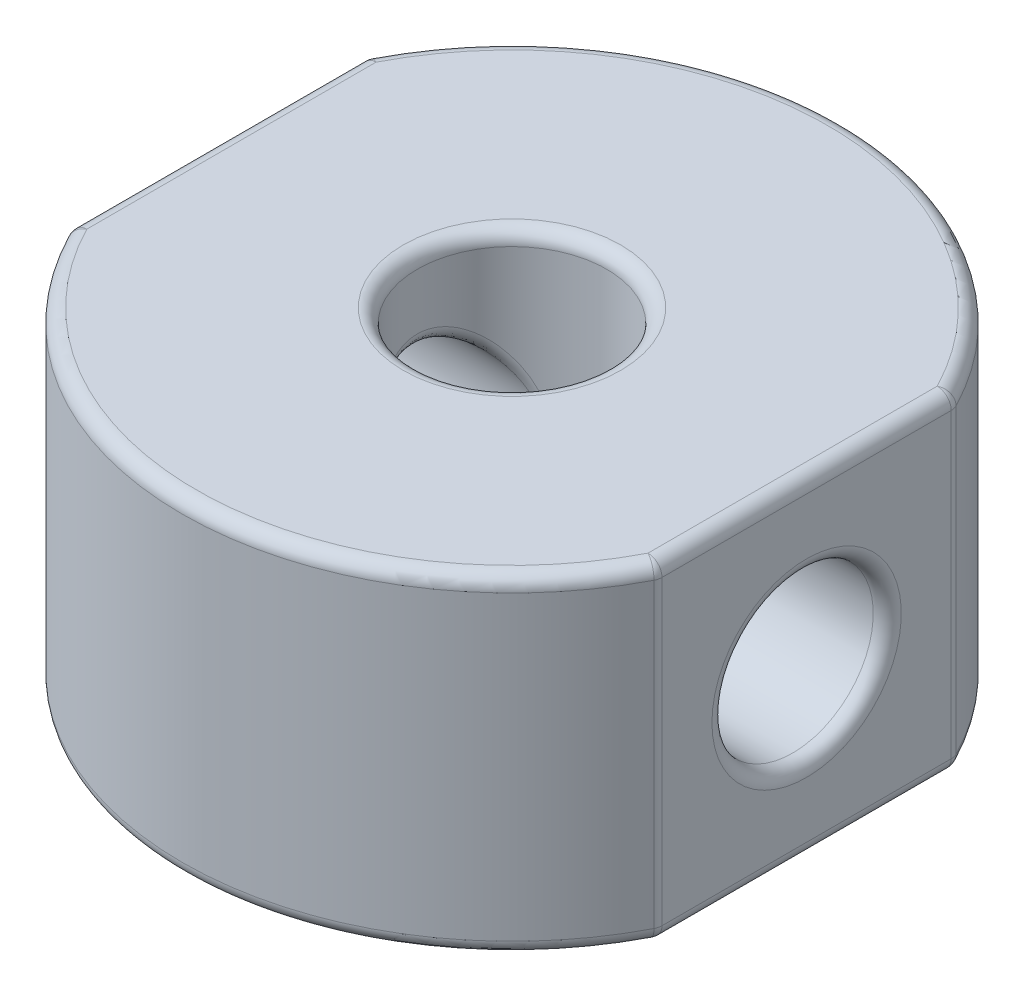
SolidWorks part; units mm, degrees
ref_plane "Front Plane" through (0, 0, 0) normal (0, 0, 1) x (1, 0, 0)
ref_plane "Top Plane" through (0, 0, 0) normal (0, 1, 0) x (1, 0, 0)
ref_plane "Right Plane" through (0, 0, 0) normal (1, 0, 0) x (0, 0, -1)
sketch "Sketch1" plane through (0, 0, 0) normal (0, 1, 0) x (1, 0, 0)
  line L0 (-2.7, 0) -> (-8.4, 0) construction
  line L1 (2.7, 0) -> (8.4, 0) construction
  line L2 (8.4, -4.219) -> (8.4, 4.219)
  line L3 (-8.4, -4.219) -> (-8.4, 4.219)
  line L4 (-8.4, 0) -> (-9.4, 0) construction
  circle A0 centre (0, 0) radius 9.4
  circle A1 centre (0, 0) radius 2.7
  point P11 (8.4, 0)
  point P14 (-8.4, 0)
  dimension "D1" = 5.4
  dimension "D2" = 5.7
  dimension "D3" = 1
extrude "Boss-Extrude1" add sketch "Sketch1" along normal blind 9.4 contours L2 A0 L3 A1
sketch "Sketch2" plane through (-8.4, 0, 0) normal (-1, 0, 0) x (0, 0, 1)
  line L0 (-4.219, 4.7) -> (0, 4.7) construction
  line L1 (-4.219, 9.4) -> (-4.219, 0) construction
  circle A0 centre (0, 4.7) radius 2.3
  dimension "D1" = 4.6
extrude "Cut-Extrude1" cut sketch "Sketch2" against normal through all
fillet "Fillet1" radius 0.4 18 edges at (-8.4, 4.7, 4.219) (-8.4, 4.7, -4.219) (8.4, 4.7, -4.219) (8.4, 4.7, 4.219) (0, 0, 9.4) (0, 0, -9.4) (-8.4, 0, 0) (8.4, 0, 0) (0, 0, 2.7) (0, 9.4, -9.4) (0, 9.4, 9.4) (-8.4, 9.4, 0) (8.4, 9.4, 0) (0, 9.4, 2.7) (8.4, 4.7, 2.3) (1.4459, 4.3988, -2.2802) (-1.4459, 5.0012, -2.2802) (-8.4, 4.7, 2.3)
